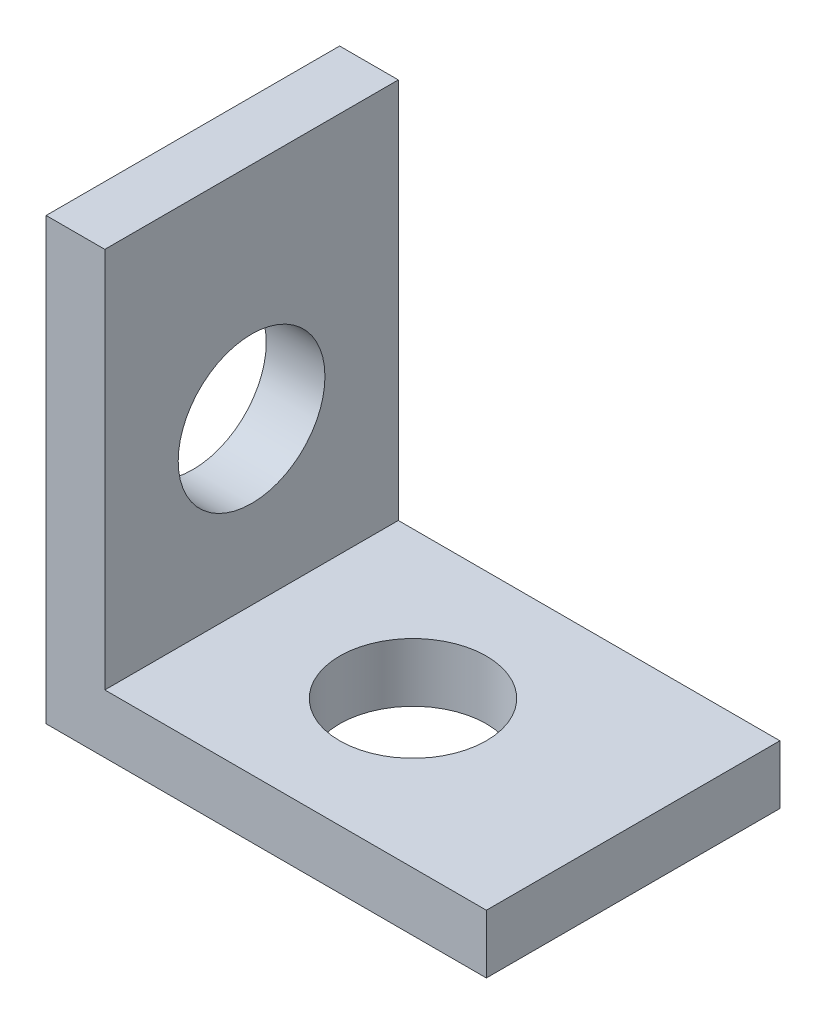
SolidWorks part; units mm, degrees
ref_plane "前视基准面" through (0, 0, 0) normal (0, 0, 1) x (1, 0, 0)
ref_plane "上视基准面" through (0, 0, 0) normal (0, 1, 0) x (1, 0, 0)
ref_plane "右视基准面" through (0, 0, 0) normal (1, 0, 0) x (0, 0, -1)
other "Configuration Table"
sketch "草图1" plane through (0, 0, 0) normal (0, 0, 1) x (1, 0, 0)
  line L0 (0, 0) -> (13, 0)
  line L1 (13, 0) -> (13, -2)
  line L2 (13, -2) -> (-2, -2)
  line L3 (-2, -2) -> (-2, 13)
  line L4 (-2, 13) -> (0, 13)
  line L6 (0, 13) -> (0, 0)
extrude "凸台-拉伸1" add sketch "草图1" along normal blind 10
sketch "草图2" plane through (0, -2, 0) normal (0, -1, 0) x (1, 0, 0)
  line L0 (-2, 5) -> (13, 5) construction
  line L1 (-2, 10) -> (-2, 0) construction
  line L2 (13, 10) -> (13, 0) construction
  circle A0 centre (5.5, 5) radius 2.5
  dimension "D1" = 7.5
extrude "切除-拉伸1" cut sketch "草图2" against normal blind 10
sketch "草图3" plane through (-2, 0, 0) normal (-1, 0, 0) x (0, 0, 1)
  line L0 (5, -2) -> (5, 13) construction
  line L1 (10, -2) -> (0, -2) construction
  line L2 (10, 13) -> (0, 13) construction
  circle A0 centre (5, 5.5) radius 2.5
  dimension "D1" = 7.5
extrude "切除-拉伸2" cut sketch "草图3" against normal blind 10
